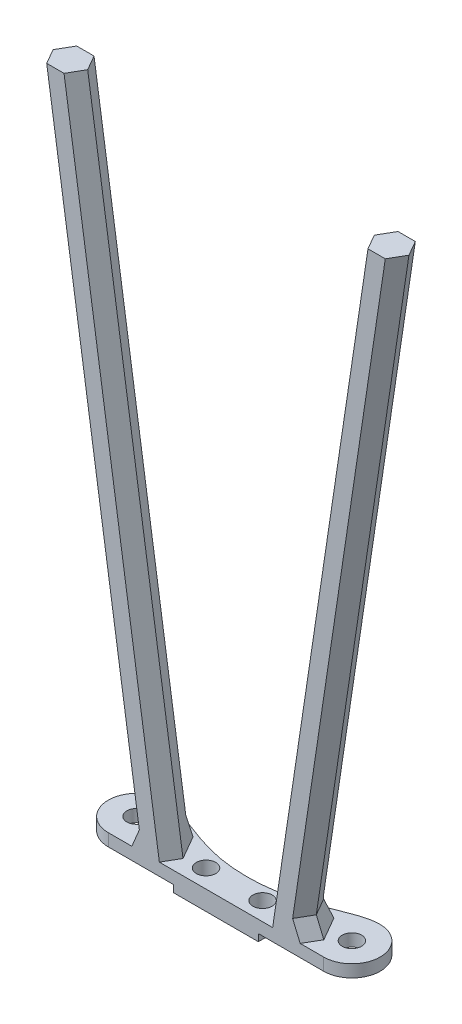
SolidWorks part; units mm, degrees
ref_plane "Front Plane" through (0, 0, 0) normal (0, 0, 1) x (1, 0, 0)
ref_plane "Top Plane" through (0, 0, 0) normal (0, 1, 0) x (1, 0, 0)
ref_plane "Right Plane" through (0, 0, 0) normal (1, 0, 0) x (0, 0, -1)
sketch "Sketch1" plane through (0, 0, 0) normal (0, 1, 0) x (1, 0, 0)
  line L0 (0, 0) -> (30.5, 0) construction
  line L1 (15.25, 0) -> (15.25, 7.3605) construction
  dimension "D1" = 30.5
sketch "Sketch2" plane through (0, 0, 0) normal (0, 1, 0) x (1, 0, 0)
  line L0 (0, 0) -> (30.5, 0) construction
  line L1 (0, 4) -> (30.5, 4)
  line L2 (0, -4) -> (30.5, -4)
  circle A0 centre (0, 0) radius 1.375
  circle A1 centre (30.5, 0) radius 1.375
  arc A2 (0, 4) -> (0, -4) centre (0, 0) ccw
  arc A3 (30.5, -4) -> (30.5, 4) centre (30.5, 0) ccw
  point P6 (15.25, 0)
  dimension "D1" = 2.75
  dimension "D2" = 2.75
  dimension "D3" = 4
extrude "Boss-Extrude1" add sketch "Sketch2" along normal blind 1.75
sketch "Sketch3" plane through (0, 1.75, 0) normal (0, 1, 0) x (1, 0, 0)
  line L2 (0, -4) -> (30.5, -4)
  line L3 (30.5, 4) -> (0, 4)
  line L4 (0, -4) -> (30.5, -4) construction
  line L5 (30.5, 4) -> (0, 4)
  arc A2 (0, 4) -> (0, -4) centre (0, 0) ccw
  arc A3 (30.5, -4) -> (30.5, 4) centre (30.5, 0) ccw
  arc A4 (0, 4) -> (0, -4) centre (0, 0) ccw construction
  arc A5 (30.5, -4) -> (30.5, 4) centre (30.5, 0) ccw construction
  spline S0 degree 3 poles (0, 4) (1.3926, 4) (4.7128, 2.7303) (11.2001, 0.2123) (19.2747, 0.2123) (25.8426, 2.7303) (29.0288, 4) (30.5, 4) knots 0 0 0 0 0.131329 0.332778 0.667222 0.868671 1 1 1 1
  dimension "D2" = 4
  dimension "D3" = 3
  dimension "D4" = 4
  dimension "D5" = 10
  dimension "D6" = 10
  dimension "D7" = 1
  dimension "D1" = 0
extrude "Cut-Extrude1" cut sketch "Sketch3" against normal blind 10
sketch "Sketch4" plane through (0, 1.75, 0) normal (0, 1, 0) x (1, 0, 0)
  line L7 (0, -4) -> (30.5, -4) construction
  line L8 (8.4537, -1.875) -> (7.2269, 0.25)
  line L9 (7.2269, 0.25) -> (4.7731, 0.25)
  line L10 (4.7731, 0.25) -> (3.5463, -1.875)
  line L11 (3.5463, -1.875) -> (4.7731, -4)
  line L12 (4.7731, -4) -> (7.2269, -4)
  line L13 (7.2269, -4) -> (8.4537, -1.875)
  circle A0 centre (6, -1.875) radius 2.125 construction
  dimension "D2" = 4.25
  dimension "D1" = 6
ref_plane "Plane1" through (0, 91.75, 0) normal (0, 1, 0) x (1, 0, 0)
sketch "Sketch5" plane through (0, 91.75, 0) normal (0, 1, 0) x (1, 0, 0)
  line L0 (0, -4) -> (30.5, -4) construction
  line L1 (-5.0463, -1.875) -> (-6.2731, 0.25)
  line L2 (-6.2731, 0.25) -> (-8.7269, 0.25)
  line L3 (-8.7269, 0.25) -> (-9.9537, -1.875)
  line L4 (-9.9537, -1.875) -> (-8.7269, -4)
  line L5 (-8.7269, -4) -> (-6.2731, -4)
  line L6 (-6.2731, -4) -> (-5.0463, -1.875)
  circle A0 centre (-7.5, -1.875) radius 2.125 construction
  dimension "D1" = 4.25
  dimension "D2" = 7.5
loft "Loft1" add profiles "Sketch4", "Sketch5"
chamfer "Chamfer1" distance 1.25 angle 70 3 edges
ref_plane "Plane2" through (15.25, 0, 0) normal (1, 0, 0) x (0, 0, -1)
mirror "Mirror1" about plane through (15.25, 0, 0) normal (1, 0, 0) of "Loft1", "Chamfer1"
sketch "Sketch6" plane through (0, 0, 0) normal (0, -1, 0) x (1, 0, 0)
  line L0 (9.25, 4) -> (9.25, -1.1867)
  line L1 (0, 4) -> (30.5, 4) construction
  line L3 (21.25, 4) -> (21.25, -1.1852)
  line L5 (9.25, 4) -> (21.25, 4)
  line L6 (30.5, 4) -> (0, 4)
  line L8 (15.25, -6.2483) -> (15.25, 6.2483) construction
  arc A2 (0, 4) -> (0, -4) centre (0, 0) ccw
  arc A3 (30.5, -4) -> (30.5, 4) centre (30.5, 0) ccw
  spline S0 degree 3 poles (0, -4) (1.3926, -4) (4.7128, -2.7303) (11.2001, -0.2123) (19.2747, -0.2123) (25.8426, -2.7303) (29.0288, -4) (30.5, -4) knots 0 0 0 0 0.131329 0.332778 0.667222 0.868671 1 1 1 1 construction
  spline S2 degree 3 poles (-489.2703, 2955.1955) (-47.3001, -21.7749) (-17.1306, -11.2087) (11.2001, -0.2123) (19.2747, -0.2123) (47.2815, -10.9495) (66.8988, -21.213) (1319.0044, 2704.7266) knots -2.246613 -2.246613 -2.246613 -2.246613 0.131329 0.332778 0.667222 0.868671 3.177953 3.177953 3.177953 3.177953 only from (0, -4) to (30.5, -4)
  spline S3 degree 3 poles (9.25, -1.1867) (9.4988, -1.1205) (13.1359, -0.2123) (17.3368, -0.2123) (21.0012, -1.1196) (21.25, -1.1852) knots 0.308101 0.308101 0.308101 0.308101 0.332778 0.667222 0.691707 0.691707 0.691707 0.691707
  point P6 (15.25, 4)
  dimension "D1" = 12
  dimension "D2" = 0
extrude "Boss-Extrude2" add sketch "Sketch6" along normal blind 1
sketch "Sketch8" plane through (0, -1, 0) normal (0, -1, 0) x (1, 0, 0)
  line L0 (9.25, 1.4066) -> (21.25, 1.4074) construction
  line L1 (9.25, 4) -> (9.25, -1.1867) construction
  line L2 (21.25, -1.1852) -> (21.25, 4) construction
  circle A0 centre (11.25, 1.4068) radius 1.375
  circle A1 centre (19.25, 1.4073) radius 1.375
  dimension "D3" = 2.75
  dimension "D1" = 2
  dimension "D2" = 2
extrude "Cut-Extrude2" cut sketch "Sketch8" against normal through all
